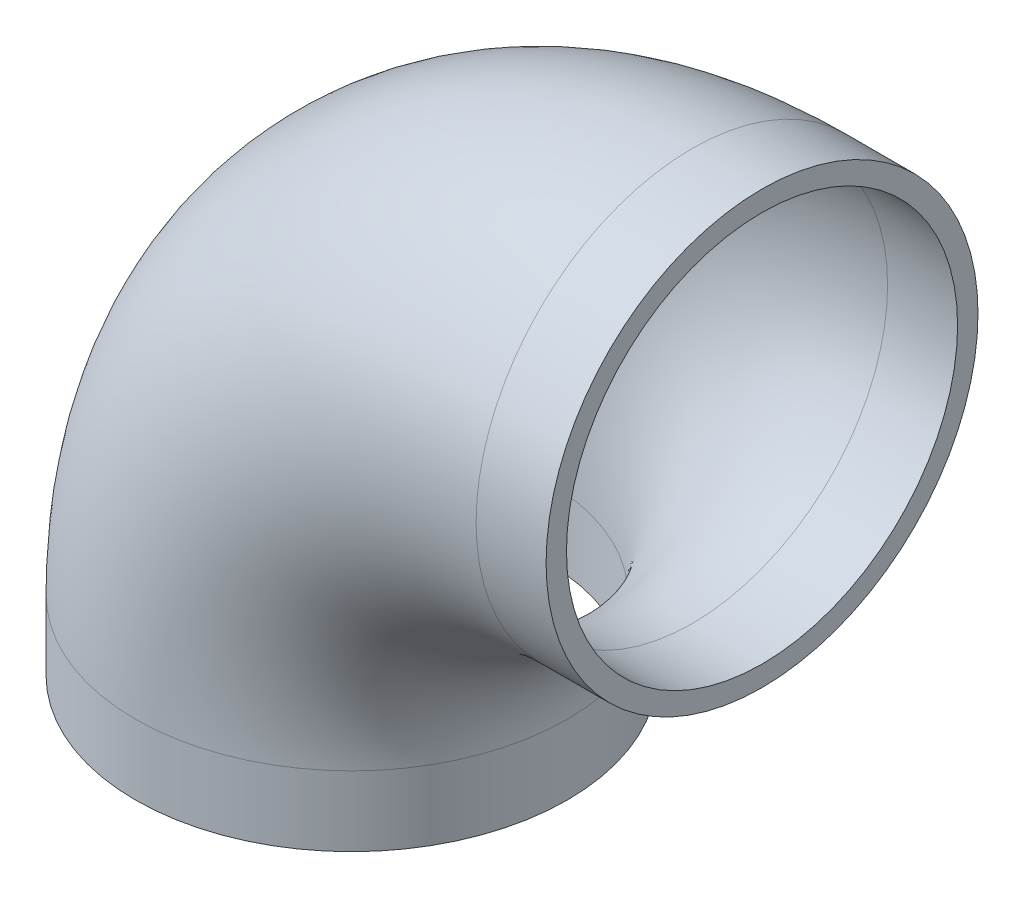
SolidWorks part; units mm, degrees
material "PVC Rígido"
ref_plane "Alzado" through (0, 0, 0) normal (0, 0, 1) x (1, 0, 0)
ref_plane "Planta" through (0, 0, 0) normal (0, 1, 0) x (1, 0, 0)
ref_plane "Vista lateral" through (0, 0, 0) normal (1, 0, 0) x (0, 0, -1)
sketch "Croquis2" plane through (0, 0, 0) normal (0, 0, 1) x (1, 0, 0)
  line L0 (0, 0) -> (0, 27.27)
  line L1 (132.73, 160) -> (160, 160)
  arc A0 (0, 27.27) -> (132.73, 160) centre (132.73, 27.27) cw
  point P6 (0, 160)
  point P9 (0, 160)
  dimension "D3" = 132.73
  dimension "D1" = 160
  dimension "D2" = 160
sketch "Croquis3" plane through (0, 0, 0) normal (0, 1, 0) x (1, 0, 0)
  circle A0 centre (0, 0) radius 84.15
  circle A1 centre (0, 0) radius 76.2
  dimension "D1" = 168.3
  dimension "D2" = 152.4
sweep "Barrer1" add profiles "Croquis3" path "Croquis2"
sketch "Croquis4" plane through (160, 0, 0) normal (1, 0, 0) x (0, 0, -1)
  circle A0 centre (0, 160) radius 94.15
  circle A1 centre (0, 160) radius 84.15
  circle A2 centre (0, 160) radius 84.15
  dimension "D2" = 10
  dimension "D1" = 0
sketch "Croquis5" plane through (0, 0, 0) normal (0, -1, 0) x (1, 0, 0)
  circle A0 centre (0, 0) radius 94.15
  circle A1 centre (0, 0) radius 84.15
  circle A2 centre (0, 0) radius 84.15
  dimension "D2" = 10
  dimension "D1" = 0
